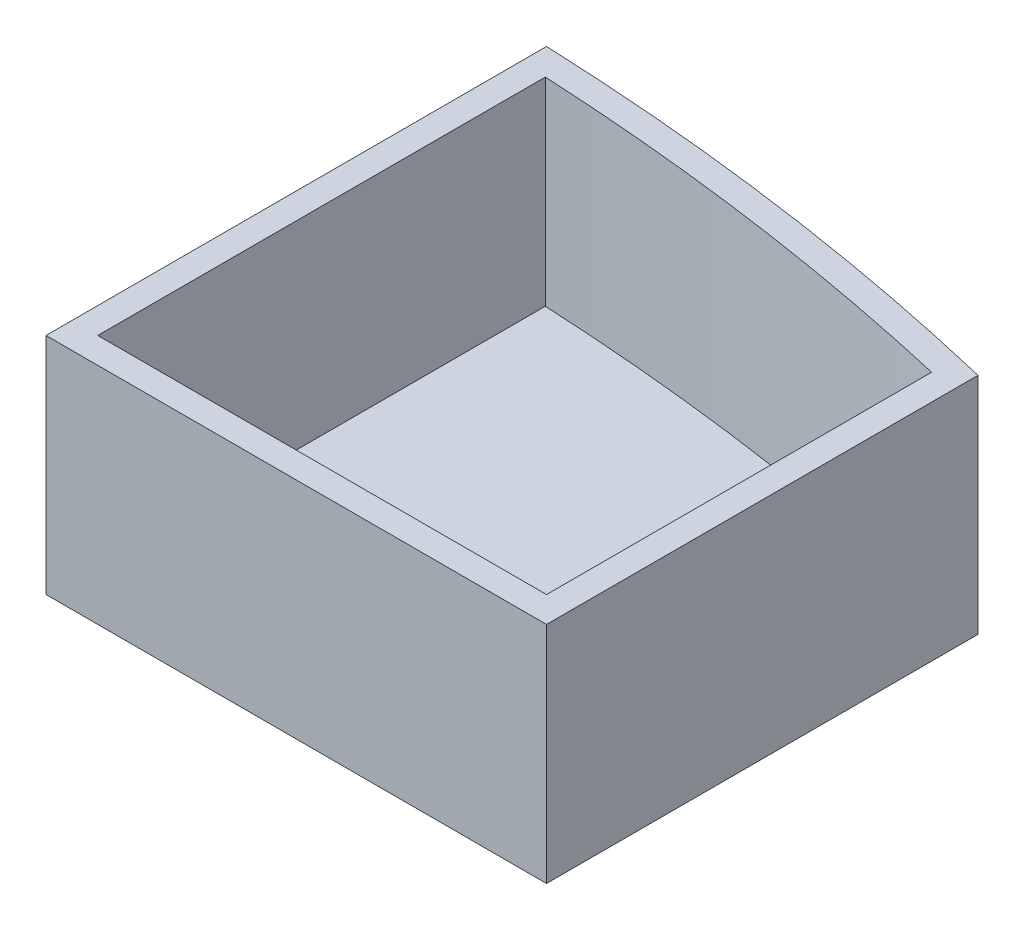
SolidWorks part; units mm, degrees
ref_plane "Front Plane" through (0, 0, 0) normal (0, 0, 1) x (1, 0, 0)
ref_plane "Top Plane" through (0, 0, 0) normal (0, 1, 0) x (1, 0, 0)
ref_plane "Right Plane" through (0, 0, 0) normal (1, 0, 0) x (0, 0, -1)
sketch "Sketch1" plane through (0, 0, 0) normal (0, 1, 0) x (1, 0, 0)
  line L0 (0, 0) -> (0, -58)
  line L1 (0, -58) -> (58, -58)
  line L2 (58, -58) -> (58, -8)
  arc A0 (0, 0) -> (58, -8) centre (-11.7956, -299.768) cw
  point P2 (45.5963, -39.4049)
  point P6 (29.8581, -0.4258)
  point P7 (15.5384, -7.3611)
  point P8 (0, 0)
  point P10 (40, -42.8729)
  point P11 (40, 0)
  point P12 (40, 0)
  point P13 (40, 0)
  point P14 (40, 0)
  point P15 (40, -4.2293)
  dimension "D1" = 300
  dimension "D2" = 58
  dimension "D3" = 58
  dimension "D4" = 50
extrude "Boss-Extrude2" add sketch "Sketch1" along normal blind 3
sketch "Sketch3" plane through (0, 3, 0) normal (0, 1, 0) x (1, 0, 0)
  line L3 (58, -58) -> (58, -8) construction
  line L4 (0, -58) -> (58, -58) construction
  line L5 (0, 0) -> (0, -58) construction
  line L6 (3, -3.1368) -> (3, -55)
  line L7 (3, -55) -> (55, -55)
  line L8 (55, -55) -> (55, -10.3767)
  line L9 (3, -3.1368) -> (3, -55)
  line L10 (3, -55) -> (55, -55)
  line L11 (55, -55) -> (55, -10.3767)
  line L12 (58, -58) -> (58, -8)
  line L13 (0, -58) -> (58, -58)
  line L14 (0, 0) -> (0, -58)
  arc A1 (58, -8) -> (0, 0) centre (-11.7956, -299.768) ccw construction
  arc A2 (55, -10.3767) -> (3, -3.1368) centre (-11.7956, -299.768) ccw
  arc A3 (55, -10.3767) -> (3, -3.1368) centre (-11.7956, -299.768) ccw
  arc A4 (58, -8) -> (0, 0) centre (-11.7956, -299.768) ccw
  dimension "D1" = 3
extrude "Boss-Extrude3" add sketch "Sketch3" along normal blind 23
ref_plane "Plane3" through (0, 13, 0) normal (0, -1, 0) x (-1, 0, 0)
sketch "Sketch10" plane through (0, 13, 0) normal (0, -1, 0) x (-1, 0, 0)
  arc A0 (0, 0) -> (-58, -8) centre (11.7956, -299.768) ccw construction
  arc A1 (0, 0) -> (-58, -8) centre (11.7956, -299.768) ccw
ref_point "Point1" parameters "D1"=10
ref_plane "Plane5" through (48.2374, 13, 5.836) normal (0.2001, 0, -0.9798) x (-0.9798, 0, -0.2001)
sketch "Sketch11" plane through (48.2374, 13, 5.836) normal (0.2001, 0, -0.9798) x (-0.9798, 0, -0.2001)
  line L0 (-9.9981, 0) -> (48.4296, 0) construction
  circle A0 centre (19.2157, 0) radius 3.5
  dimension "D1" = 7
extrude "Boss-Extrude5" add sketch "Sketch11" along normal blind 7 and the other way up to next
